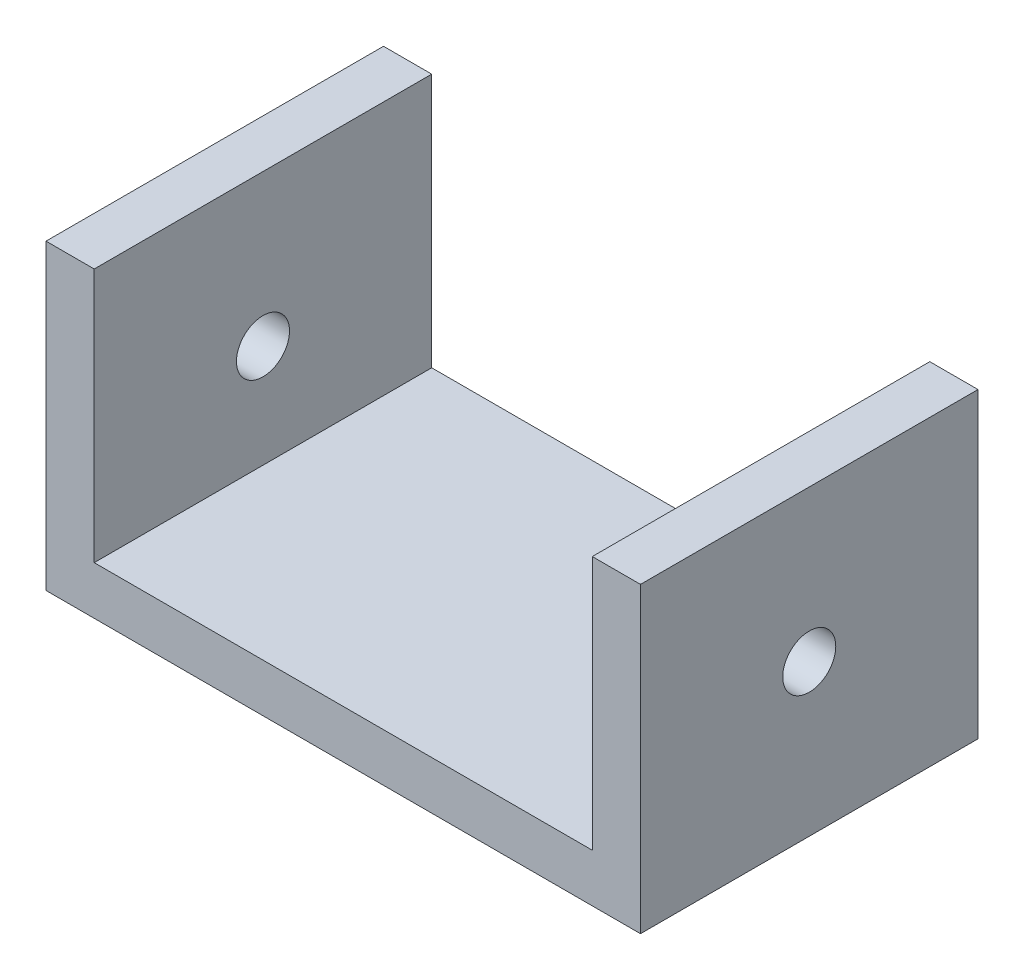
SolidWorks part; units mm, degrees
ref_plane "Front Plane" through (0, 0, 0) normal (0, 0, 1) x (1, 0, 0)
ref_plane "Top Plane" through (0, 0, 0) normal (0, 1, 0) x (1, 0, 0)
ref_plane "Right Plane" through (0, 0, 0) normal (1, 0, 0) x (0, 0, -1)
sketch "Sketch1" plane through (0, 0, 0) normal (0, 0, 1) x (1, 0, 0)
  line L1 (-30.825, 15.6875) -> (30.825, 15.6875)
  line L2 (-30.825, 15.6875) -> (-30.825, -15.6875)
  line L3 (-30.825, -15.6875) -> (30.825, -15.6875)
  line L4 (30.825, 15.6875) -> (30.825, -15.6875)
  line L5 (0, -15.6875) -> (0, 15.6875) construction
  line L6 (-30.825, 0) -> (30.825, 0) construction
  point P0 (0, 0)
  dimension "D1" = 61.65
  dimension "D2" = 31.375
extrude "Boss-Extrude1" add sketch "Sketch1" along normal blind 35
sketch "Sketch2" plane through (0, 0, 0) normal (0, 0, -1) x (-1, 0, 0)
  line L0 (-30.825, 15.6875) -> (30.825, 15.6875) construction
  line L1 (-25.825, 15.6875) -> (25.825, 15.6875)
  line L2 (-25.825, 15.6875) -> (-25.825, -10.6875)
  line L3 (-25.825, -10.6875) -> (25.825, -10.6875)
  line L4 (25.825, 15.6875) -> (25.825, -10.6875)
  line L5 (-30.825, -15.6875) -> (-30.825, 15.6875) construction
  line L6 (30.825, 15.6875) -> (30.825, -15.6875) construction
  line L7 (30.825, -15.6875) -> (-30.825, -15.6875) construction
  dimension "D1" = 5
  dimension "D2" = 5
  dimension "D3" = 5
extrude "Cut-Extrude1" cut sketch "Sketch2" against normal through all
sketch "Sketch3" plane through (30.825, 0, 0) normal (1, 0, 0) x (0, 0, -1)
  line L0 (-35, 15.6875) -> (0, 15.6875) construction
  line L1 (0, -15.6875) -> (0, 15.6875) construction
  circle A0 centre (-17.5, 0) radius 2.75
  dimension "D1" = 15.6875
  dimension "D2" = 17.5
extrude "Cut-Extrude2" cut sketch "Sketch3" against normal through all
